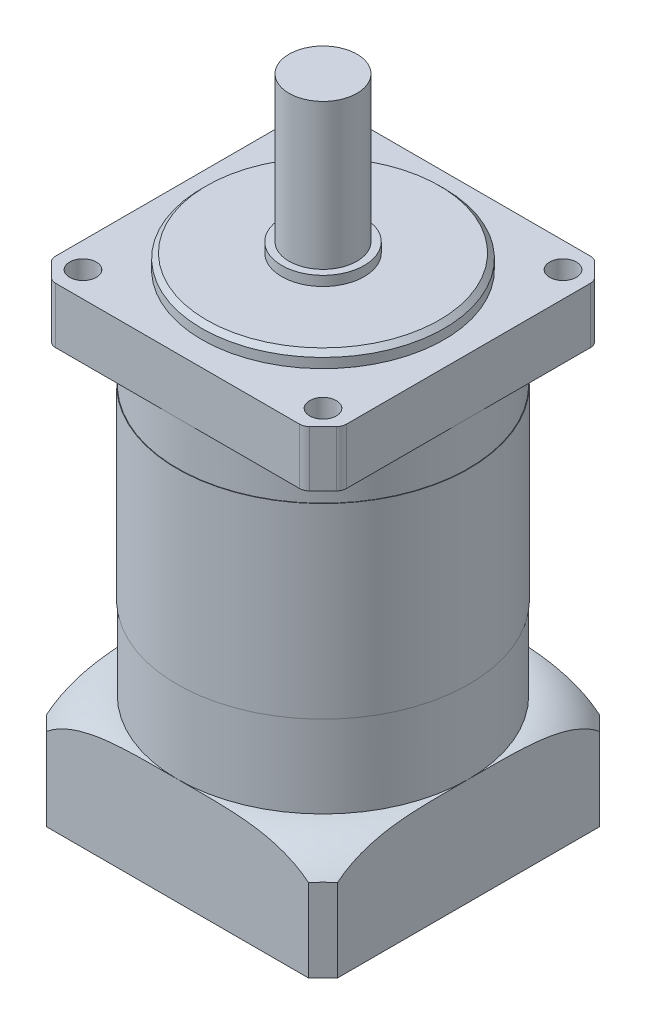
SolidWorks part; units mm, degrees
material "1.0037 (S235JR)"
ref_plane "Ön Düzlem" through (0, 0, 0) normal (0, 0, 1) x (1, 0, 0)
ref_plane "Üst Düzlem" through (0, 0, 0) normal (0, 1, 0) x (1, 0, 0)
ref_plane "Sağ Düzlem" through (0, 0, 0) normal (1, 0, 0) x (0, 0, -1)
sketch "Çizim1" plane through (0, 0, 0) normal (0, 1, 0) x (1, 0, 0)
  line L1 (-30, 30) -> (30, 30)
  line L2 (-30, 30) -> (-30, -30)
  line L3 (-30, -30) -> (30, -30)
  line L4 (30, 30) -> (30, -30)
  line L5 (-30, 30) -> (30, -30) construction
  line L6 (-30, -30) -> (30, 30) construction
  point P0 (0, 0)
  dimension "D1" = 60
  dimension "D2" = 60
extrude "Yükseklik-Ekstrüzyon1" add sketch "Çizim1" along normal blind 11.5
chamfer "Pah1" distance 4 angle 45 4 edges at (-30, 5.75, -30) (-30, 5.75, 30) (30, 5.75, -30) (30, 5.75, 30)
sketch "Çizim2" plane through (0, 11.5, 0) normal (0, 1, 0) x (1, 0, 0)
  circle A0 centre (0, 0) radius 25
  dimension "D1" = 50
extrude "Yükseklik-Ekstrüzyon2" add sketch "Çizim2" along normal blind 3
chamfer "Pah2" distance 1 angle 45 1 edges at (0, 14.5, 25)
fillet "Radyus1" radius 2 8 edges at (26, 5.75, -30) (30, 5.75, -26) (-30, 5.75, -26) (-26, 5.75, -30) (30, 5.75, 26) (26, 5.75, 30) (-30, 5.75, 26) (-26, 5.75, 30)
sketch "Çizim3" plane through (0, 0, 0) normal (0, -1, 0) x (1, 0, 0)
  circle A0 centre (0, 0) radius 30
  dimension "D1" = 60
extrude "Yükseklik-Ekstrüzyon3" add sketch "Çizim3" along normal blind 64.5
sketch "Çizim4" plane through (0, -64.5, 0) normal (0, -1, 0) x (1, 0, 0)
  line L1 (-30, 30) -> (30, 30)
  line L2 (-30, 30) -> (-30, -30)
  line L3 (-30, -30) -> (30, -30)
  line L4 (30, 30) -> (30, -30)
  line L5 (-30, 30) -> (30, -30) construction
  line L6 (-30, -30) -> (30, 30) construction
  point P0 (0, 0)
  dimension "D1" = 60
  dimension "D2" = 60
extrude "Yükseklik-Ekstrüzyon4" add sketch "Çizim4" along normal blind 22
chamfer "Pah3" distance 3 angle 45 4 edges at (30, -75.5, -30) (-30, -75.5, -30) (-30, -75.5, 30) (30, -75.5, 30)
sketch "Çizim8" plane through (0, 0, 0) normal (1, 0, 0) x (0, 0, -1)
  line L0 (-30, -86.5) -> (-30, -64.5) construction
  line L1 (0, -64.5) -> (-27, -64.5) construction
  line L2 (0, -64.5) -> (-30, -64.5) construction
  line L3 (-30, -64.5) -> (-40.4, -64.5)
  line L4 (-40.4, -64.5) -> (-40.4, -69.5)
  line L5 (0, -86.5) -> (0, -54.122) construction
  line L6 (27, -86.5) -> (-27, -86.5) construction
  arc A0 (-40.4, -69.5) -> (-30, -64.5) centre (-30, -77.816) cw
  dimension "D1" = 10.4
  dimension "D2" = 5
revolve "Kes-Döndür2" cut sketch "Çizim8" angle 360 about L5
sketch "Çizim9" plane through (0, -86.5, 0) normal (0, -1, 0) x (1, 0, 0)
  line L1 (-28, 28) -> (28, 28)
  line L2 (-28, 28) -> (-28, -28)
  line L3 (-28, -28) -> (28, -28)
  line L4 (28, 28) -> (28, -28)
  line L5 (-28, 28) -> (28, -28) construction
  line L6 (-28, -28) -> (28, 28) construction
  point P0 (0, 0)
  dimension "D1" = 56
  dimension "D2" = 56
extrude "Yükseklik-Ekstrüzyon5" [suppressed] add sketch "Çizim9" along normal blind 4.7
fillet "Radyus2" [suppressed] radius 3
sketch "Çizim10" [suppressed] plane through (0, -91.2, 0) normal (0, -1, 0) x (1, 0, 0)
  circle A0 centre (0, 0) radius 28
  dimension "D1" = 56
extrude "Yükseklik-Ekstrüzyon6" [suppressed] add sketch "Çizim10" along normal blind 10
sketch "Çizim11" [suppressed] plane through (0, -101.2, 0) normal (0, -1, 0) x (1, 0, 0)
  circle A0 centre (0, 0) radius 27.5
  dimension "D1" = 55
extrude "Yükseklik-Ekstrüzyon7" [suppressed] add sketch "Çizim11" along normal blind 76.75
sketch "Çizim12" [suppressed] plane through (0, -177.95, 0) normal (0, -1, 0) x (1, 0, 0)
  circle A0 centre (0, 0) radius 28
  circle A1 centre (0, 0) radius 28 construction
extrude "Yükseklik-Ekstrüzyon8" [suppressed] add sketch "Çizim12" along normal blind 22
sketch "Çizim14" [suppressed] plane through (0, -199.95, 0) normal (0, -1, 0) x (1, 0, 0)
  circle A0 centre (0, 0) radius 28.5
  dimension "D1" = 57
extrude "Yükseklik-Ekstrüzyon9" [suppressed] add sketch "Çizim14" along normal blind 19.55
ref_plane "Düzlem1" [suppressed] through (0, 0, 28.5) normal (0, 0, 1) x (1, 0, 0)
sketch "Çizim15" [suppressed] plane through (0, 0, 28.5) normal (0, 0, 1) x (1, 0, 0)
  line L0 (0, -199.95) -> (0, -219.5) construction
  line L1 (28.5, -199.95) -> (-28.5, -199.95) construction
  line L2 (-28.5, -219.5) -> (28.5, -219.5) construction
  line L4 (-15, -200.225) -> (15, -200.225)
  line L5 (-15, -200.225) -> (-15, -219.225)
  line L6 (-15, -219.225) -> (15, -219.225)
  line L7 (15, -200.225) -> (15, -219.225)
  line L8 (-15, -200.225) -> (15, -219.225) construction
  line L9 (-15, -219.225) -> (15, -200.225) construction
  point P6 (0, -209.725)
  dimension "D1" = 30
  dimension "D2" = 19
extrude "Yükseklik-Ekstrüzyon10" [suppressed] add sketch "Çizim15" along normal blind 5 and the other way up to surface
fillet "Radyus3" [suppressed] radius 4.3
sketch "Çizim17" [suppressed] plane through (0, -200.225, 0) normal (0, 1, 0) x (1, 0, 0)
  line L0 (0, -33.5) -> (0, -36.5) construction
  line L1 (5, -33.5) -> (-5, -33.5) construction
  line L2 (-5, -33.5) -> (-5, -36.5)
  line L3 (5, -33.5) -> (5, -36.5)
  line L4 (-5, -36.5) -> (5, -36.5)
  line L5 (-5, -33.5) -> (5, -33.5)
  dimension "D1" = 3
  dimension "D2" = 5
  dimension "D3" = 5
extrude "Yükseklik-Ekstrüzyon11" [suppressed] add sketch "Çizim17" against normal up to vertex
fillet "Radyus4" [suppressed] radius 1.5
fillet "Radyus5" [suppressed] radius 5
sketch "Çizim19" plane through (0, 14.5, 0) normal (0, 1, 0) x (1, 0, 0)
  circle A0 centre (0, 0) radius 8.5
  dimension "D1" = 17
extrude "Yükseklik-Ekstrüzyon12" add sketch "Çizim19" along normal blind 2
sketch "Çizim20" plane through (0, 16.5, 0) normal (0, 1, 0) x (1, 0, 0)
  circle A0 centre (0, 0) radius 7
  dimension "D1" = 14
extrude "Yükseklik-Ekstrüzyon13" add sketch "Çizim20" along normal blind 30
ref_plane "Düzlem2" through (0, 0, 7) normal (0, 0, 1) x (1, 0, 0)
sketch "Çizim21" plane through (0, 0, 7) normal (0, 0, 1) x (1, 0, 0)
  line L0 (0, 41) -> (0, 26) construction
  line L1 (2.5, 41) -> (2.5, 26)
  line L2 (-2.5, 41) -> (-2.5, 26)
  line L3 (7, 46.5) -> (-7, 46.5) construction
  arc A0 (2.5, 41) -> (-2.5, 41) centre (0, 41) ccw
  arc A1 (-2.5, 26) -> (2.5, 26) centre (0, 26) ccw
  point P2 (0, 33.5)
  dimension "D1" = 2.5
  dimension "D3" = 5.5
  dimension "D2" = 15
sketch "Çizim22" plane through (0, 11.5, 0) normal (0, 1, 0) x (1, 0, 0)
  line L0 (-24.7487, 24.7487) -> (0, 0) construction
  line L1 (0, 0) -> (-11.2719, 0) construction
  circle A0 centre (0, 0) radius 35 construction
  circle A1 centre (-24.7487, 24.7487) radius 2.75
  circle A2 centre (24.7487, 24.7487) radius 2.75
  circle A3 centre (24.7487, -24.7487) radius 2.75
  circle A4 centre (-24.7487, -24.7487) radius 2.75
  point P15 (0, 0)
  dimension "D1" = 70
  dimension "D3" = 5.5
  dimension "D2" = 45
  dimension "D4" = 4
extrude "Kes-Ekstrüzyon2" cut sketch "Çizim22" against normal up to surface (11.5 mm away) up to face at (-24.5973, 0, -24.5973)
sketch "Çizim23" plane through (0, 0, 0) normal (0, 0, 1) x (1, 0, 0)
  line L0 (-30, -9) -> (-30, -47.5)
  line L1 (-30, 0) -> (-30, -64.5) construction
  line L2 (-30, -47.5) -> (-30.1, -47.5)
  line L3 (-30.1, -47.5) -> (-30.1, -9)
  line L4 (-30.1, -9) -> (-30, -9)
  line L5 (-30, 0) -> (0, 0) construction
  line L6 (0, -64.5) -> (-30, -64.5) construction
  line L7 (0, -64.5) -> (0, -47.5) construction
  dimension "D1" = 0.1
  dimension "D2" = 9
  dimension "D3" = 17
revolve "Döndür1" add sketch "Çizim23" angle 360 about L7
sketch "Çizim24" plane through (0, -86.5, 0) normal (0, -1, 0) x (1, 0, 0)
  line L8 (-27, -30) -> (27, -30)
  line L9 (27, -30) -> (30, -27)
  line L10 (30, -27) -> (30, 27)
  line L11 (30, 27) -> (27, 30)
  line L12 (27, 30) -> (-27, 30)
  line L13 (-27, 30) -> (-30, 27)
  line L14 (-30, 27) -> (-30, -27)
  line L15 (-30, -27) -> (-27, -30)
  line L16 (-27, -30) -> (27, -30)
  line L17 (27, -30) -> (30, -27)
  line L18 (30, -27) -> (30, 27)
  line L19 (30, 27) -> (27, 30)
  line L20 (27, 30) -> (-27, 30)
  line L21 (-27, 30) -> (-30, 27)
  line L22 (-30, 27) -> (-30, -27)
  line L23 (-30, -27) -> (-27, -30)
  dimension "D1" = 0
extrude "Kes-Ekstrüzyon3" [suppressed] cut sketch "Çizim24" against normal up to vertex
sketch "Çizim25" plane through (0, -86.5, 0) normal (0, -1, 0) x (-1, 0, 0)
  circle A0 centre (23.55, -23.55) radius 2.6
  circle A1 centre (-23.55, -23.55) radius 2.6
  circle A2 centre (23.55, 23.55) radius 2.6
  circle A3 centre (-23.55, 23.55) radius 2.6
  dimension "D1" = 5.2
extrude "Kes-Ekstrüzyon4" cut sketch "Çizim25" against normal blind 10
